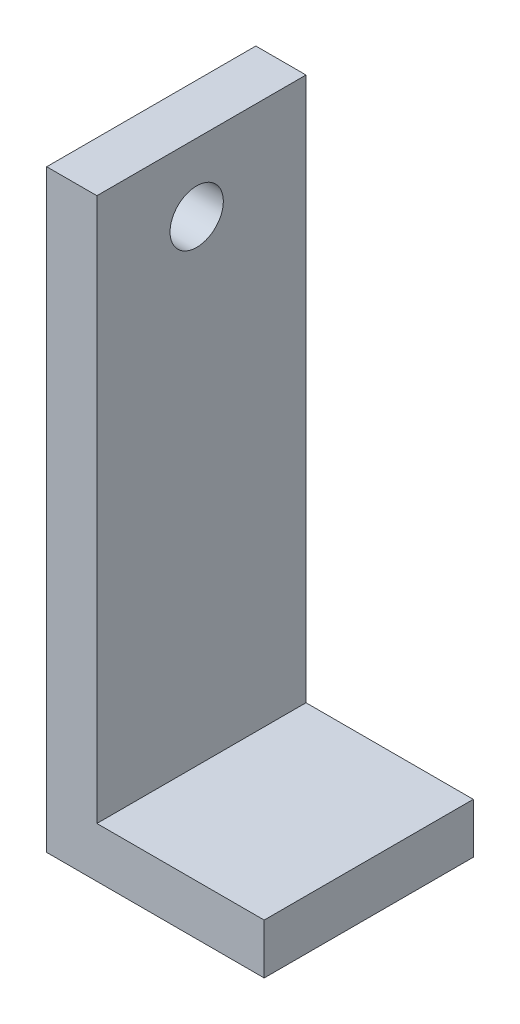
SolidWorks part; units mm, degrees
ref_plane "Front Plane" through (0, 0, 0) normal (0, 0, 1) x (1, 0, 0)
ref_plane "Top Plane" through (0, 0, 0) normal (0, 1, 0) x (1, 0, 0)
ref_plane "Right Plane" through (0, 0, 0) normal (1, 0, 0) x (0, 0, -1)
sketch "Sketch1" plane through (0, 0, 0) normal (1, 0, 0) x (0, 0, -1)
  line L1 (0, 0) -> (-25, 0)
  line L2 (0, 0) -> (0, -71)
  line L3 (0, -71) -> (-25, -71)
  line L4 (-25, 0) -> (-25, -71)
  dimension "D1" = 25
  dimension "D2" = 71
extrude "Boss-Extrude1" add sketch "Sketch1" along normal blind 6
sketch "Sketch2" plane through (6, 0, 0) normal (1, 0, 0) x (0, 0, -1)
  line L0 (0, -71) -> (0, 0) construction
  line L1 (-25, -71) -> (0, -71)
  line L2 (-25, -71) -> (-25, -65)
  line L3 (-25, -65) -> (0, -65)
  line L4 (0, -71) -> (0, -65)
  dimension "D1" = 6
extrude "Boss-Extrude2" add sketch "Sketch2" along normal blind 20
sketch "Sketch3" plane through (6, 0, 0) normal (1, 0, 0) x (0, 0, -1)
  circle A0 centre (-13.0702, -8.1295) radius 3.1876
extrude "Cut-Extrude1" cut sketch "Sketch3" against normal blind 22.5
